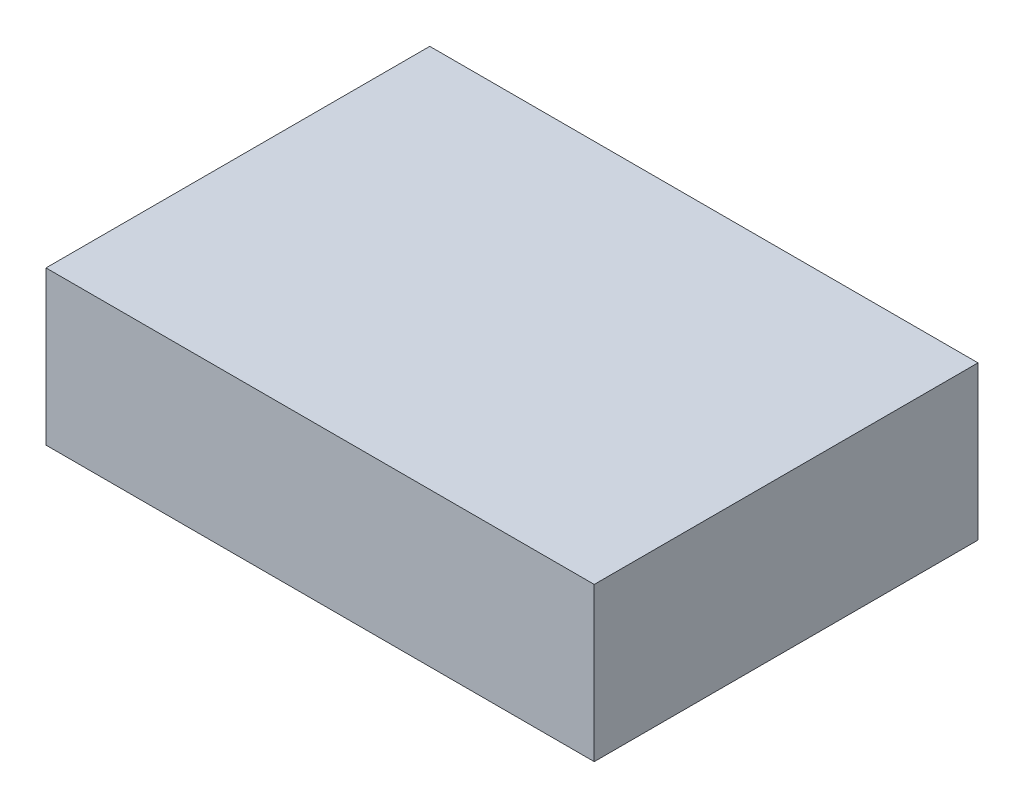
SolidWorks part; units mm, degrees
material "ABS"
ref_plane "Front Plane" through (0, 0, 0) normal (0, 0, 1) x (1, 0, 0)
ref_plane "Top Plane" through (0, 0, 0) normal (0, 1, 0) x (1, 0, 0)
ref_plane "Right Plane" through (0, 0, 0) normal (1, 0, 0) x (0, 0, -1)
sketch "Sketch1" plane through (0, 0, 0) normal (0, 1, 0) x (1, 0, 0)
  line L1 (0, 0) -> (100, 0)
  line L2 (0, 0) -> (0, -70)
  line L3 (0, -70) -> (100, -70)
  line L4 (100, 0) -> (100, -70)
  dimension "D1" = 70
  dimension "D2" = 100
extrude "Boss-Extrude1" add sketch "Sketch1" along normal blind 28
